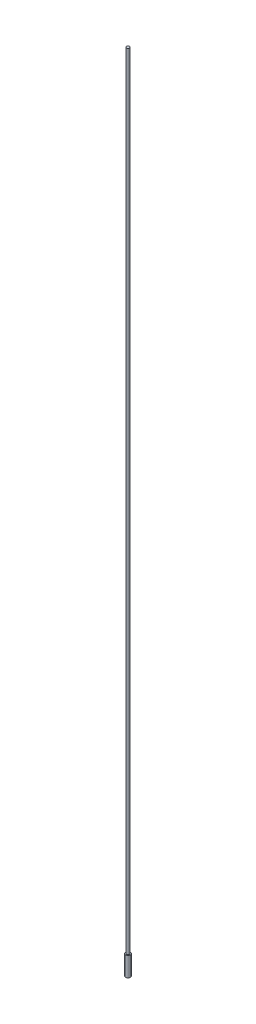
SolidWorks part; units mm, degrees
ref_plane "Front Plane" through (0, 0, 0) normal (0, 0, 1) x (1, 0, 0)
ref_plane "Top Plane" through (0, 0, 0) normal (0, 1, 0) x (1, 0, 0)
ref_plane "Right Plane" through (0, 0, 0) normal (1, 0, 0) x (0, 0, -1)
sketch "Sketch1" plane through (0, 0, 0) normal (0, 1, 0) x (1, 0, 0)
  circle A0 centre (0, 0) radius 1.25
  dimension "D1" = 2.5
extrude "Boss-Extrude1" add sketch "Sketch1" along normal blind 701.675
sketch "Sketch2" plane through (0, 0, 0) normal (0, -1, 0) x (1, 0, 0)
  circle A0 centre (0, 0) radius 2.1
  dimension "D1" = 4.2
extrude "Boss-Extrude2" add sketch "Sketch2" against normal blind 17
